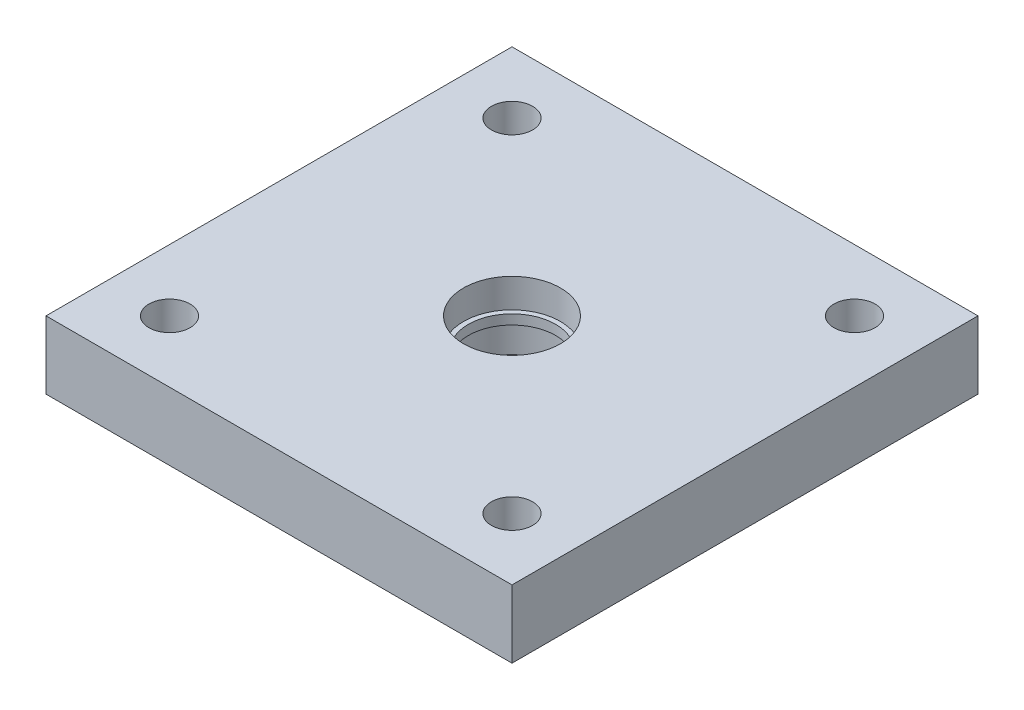
SolidWorks part; units mm, degrees
material "1060 Alloy"
ref_plane "Front" through (0, 0, 0) normal (0, 0, 1) x (1, 0, 0)
ref_plane "Top" through (0, 0, 0) normal (0, 1, 0) x (1, 0, 0)
ref_plane "Right" through (0, 0, 0) normal (1, 0, 0) x (0, 0, -1)
sketch "Sketch1" plane through (0, 0, 0) normal (0, 1, 0) x (1, 0, 0)
  line L1 (-48.1053, 48.1053) -> (48.1053, 48.1053)
  line L2 (-48.1053, 48.1053) -> (-48.1053, -48.1053)
  line L3 (-48.1053, -48.1053) -> (48.1053, -48.1053)
  line L4 (48.1053, 48.1053) -> (48.1053, -48.1053)
  line L5 (-48.1053, 48.1053) -> (48.1053, -48.1053) construction
  line L6 (-48.1053, -48.1053) -> (48.1053, 48.1053) construction
  circle A0 centre (-35.3553, 35.3553) radius 4.25
  circle A1 centre (35.3553, 35.3553) radius 4.25
  circle A2 centre (35.3553, -35.3553) radius 4.25
  circle A3 centre (-35.3553, -35.3553) radius 4.25
  circle A4 centre (0, 0) radius 9
  point P0 (0, 0)
  point P17 (0, 0)
  dimension "D3" = 8.5
  dimension "D7" = 18
  dimension "D2" = 50
  dimension "D5" = 50
  dimension "D6" = 50
  dimension "D1" = 12.75
  dimension "D4" = 4
extrude "body and main holes" add sketch "Sketch1" along normal blind 14
sketch "Sketch2" plane through (0, 14, 0) normal (0, 1, 0) x (1, 0, 0)
  circle A0 centre (0, 0) radius 10
  dimension "D1" = 20
extrude "seal hole" cut sketch "Sketch2" against normal blind 6
sketch "Sketch3" plane through (0, 0, 0) normal (0, -1, 0) x (1, 0, 0)
  circle A0 centre (0, 0) radius 10
  dimension "D1" = 20
extrude "bearing hole" cut sketch "Sketch3" against normal blind 6
sketch "Sketch4" plane through (0, 0, 0) normal (0, -1, 0) x (1, 0, 0)
  circle A0 centre (0, 0) radius 15 construction
  circle A1 centre (0, -15) radius 2
  circle A2 centre (-15, 0) radius 2
  circle A3 centre (0, 15) radius 2
  circle A4 centre (15, 0) radius 2
  point P14 (0, 0)
  dimension "D1" = 30
  dimension "D2" = 4
  dimension "D3" = 4
extrude "Cut-Extrude1" cut sketch "Sketch4" against normal blind 10
equation "\"motor mount pattern diameter\"= 30mm"
equation "\"D2@Sketch1\" = \"motor mount to housing m8 pattern diameter\" / 2"
equation "\"D3@Sketch1\" = \"motor mount to housing m8 screw hole diameter\""
equation "\"D5@Sketch1\" = \"motor mount to housing m8 pattern diameter\" / 2"
equation "\"D6@Sketch1\" = \"motor mount to housing m8 pattern diameter\" / 2"
equation "\"D1@Sketch1\" = \"motor mount to housing m8 screw post radius\""
equation "\"D1@body and main holes\" = \"housing base thickness\""
equation "\"D1@Sketch2\" = \"seal OD\""
equation "\"D1@seal hole\" = \"seal depth\""
equation "\"D1@Sketch3\" = \"bearing OD\""
equation "\"D1@bearing hole\" = \"bearing depth\""
equation "\"bearing OD\" = 20mm"
equation "\"bearing outer race thickness\"= 1mm"
equation "\"bearing ID\"= 10mm"
equation "\"bearing depth\"= 6mm"
equation "\"bearing inner race thickness\"= 1mm"
equation "\"seal OD\" = 20mm"
equation "\"seal ID\"= 8mm"
equation "\"seal depth\"= 6mm"
equation "\"impeller base outer diameter\"= 1.75in"
equation "\"impeller base outer thickness\"= 1mm"
equation "\"impeller base center thickness\"= 5mm"
equation "\"impeller number of vanes\"= 8"
equation "\"impeller vane inner height\"= 8mm"
equation "\"impeller primary vane opening diamater\"= 10mm"
equation "\"impeller vane inner thickness\"= .75mm"
equation "\"impeller vane outer thickness\"= 1.5mm"
equation "\"impeller primary vane entrance angle\"= 20deg"
equation "\"impeller secondary vane entrance angle\"= 20deg"
equation "\"impeller secondary vane opening diameter\"= 10mm"
equation "\"motor to housing distance\"= 60mm"
equation "\"motor mount coupler shaft hole diameter\"= \"coupler shaft base diameter\"+ 4mm"
equation "\"motor mount to housing m8 screw hole diameter\"= 8.5mm"
equation "\"motor mount to housing m8 screw post radius\"= ( 3 * \"motor mount to housing m8 screw hole diameter\" ) / 2"
equation "\"motor mount to housing m8 pattern diameter\"= 100mm"
equation "\"motor mount to housing m4 screw hole diamater\"= 4mm"
equation "\"motor mount to housing m4 head diameter\"= 7.25mm"
equation "\"motor mount to housing m4 head depth\"= 4mm"
equation "\"motor mount plate thickness\"= 6mm + \"motor mount to housing m4 head depth\""
equation "\"coupler shaft set screw 1 distance\"= \"motor mount shaft hole depth\" / 3"
equation "\"coupler shaft set screw 2 distance\"= \"motor mount shaft hole depth\" * 4 / 5"
equation "\"housing bearing seat lip thickness\" = 2mm"
equation "\"housing base thickness\"= \"housing bearing seat lip thickness\" + \"seal depth\" + \"bearing depth\""
equation "\"housing top impeller vertical clearance\"= .5mm"
equation "\"housing top impeller horizontal clearance\"= .5mm"
equation "\"housing top impeller bottom clearance\"= 1mm"
equation "\"housing top impeller cavity height\"= \"housing top impeller bottom clearance\" + \"impeller base center thickness\" + \"impeller vane inner height\" + \"housing top impeller vertical clearance\""
equation "\"housing top impeller cavity diameter\"= 2 * \"housing top impeller horizontal clearance\" + \"impeller base outer diameter\""
equation "\"housing top impeller cavity tip height\"= \"housing top impeller bottom clearance\" + \"housing top impeller vertical clearance\" + \"impeller base outer thickness\" + \"impeller vane outer height\""
equation "\"housing top entrance OD\"= 20mm"
equation "\"housing top exit OD\"= 5mm"
equation "\"housing top o-ring channel height\"= 1.5mm"
equation "\"housing top o ring channel width\"= 1.5mm"
equation "\"housing top threaded inlet depth\"= 8mm"
equation "\"housing top total thickness\"= \"housing top threaded inlet depth\" + \"housing top impeller cavity height\""
equation "\"housing top total width\"= 10mm"
equation "\"housing top exit threaded diameter\"= 8mm"
equation "\"housing top exit threaded depth\"= 8mm"
equation "\"motor shaft pride\"= 32mm"
equation "\"motor shaft flat section length from tip\"= 25.7mm"
equation "\"motor shaft bore end clearance\"= 2mm"
equation "\"motor mount shaft hole depth\"= \"motor shaft pride\""
equation "\"coupler shaft set screw drill hole diameter\"= 6mm"
equation "\"coupler shaft motor shaft hole diameter\"= 8mm"
equation "\"coupler shaft base diameter\"= 18mm"
equation "\"coupler shaft base length\"= \"motor mount shaft hole depth\" + 10mm"
equation "\"coupler shaft second section diameter\"= \"bearing ID\" + \"bearing inner race thickness\" * 2"
equation "\"coupler shaft second section length\"= \"motor to housing distance\" -  \"coupler shaft base length\" - 2mm"
equation "\"coupler shaft third section diamater\"= \"bearing ID\""
equation "\"coupler shaft third section length\"= \"bearing depth\""
equation "\"coupler shaft seal section diameter\" = \"seal ID\""
equation "\"coupler shaft seal section length\" = \"housing base thickness\"+\"housing top impeller bottom clearance\"-\"bearing depth\""
equation "\"coupler shaft impeller section diameter\" = 6mm"
equation "\"coupler shaft impeller section length\" = \"impeller boss depth\"+\"impeller base center thickness\" - 1mm"
equation "\"coupler shaft impeller screw hole diameter\" = \"motor mount to housing m4 screw hole diamater\""
equation "\"coupler shaft impeller screw hole depth\" = 10mm"
equation "\"D7@Sketch1\"=\"bearing OD\"-\"bearing outer race thickness\"*2"
equation "\"D1@Sketch4\"=\"bearing OD\"+ 10mm"
equation "\"D2@Sketch4\"=\"motor mount to housing m4 screw hole diamater\""
equation "\"D1@Cut-Extrude1\"=\"housing base thickness\"-4mm"
equation "\"impeller vane outer height\"= 4mm"
equation "\"impeller bolt surface height\" = 5mm"
equation "\"impeller bolt surface diameter\" = 8mm"
equation "\"impeller boss depth\" = 5mm"
equation "\"impeller dowel diameter\" = 2mm"
equation "\"housing top o-ring circumference\" = 250mm"
equation "\"housing top o-ring radius\" = (\"housing top o-ring circumference\")/(2*3.14)"
equation "\"coupler shaft to motor clearance\" = 2mm"
equation "\"impeller boss diameter\" = \"coupler shaft impeller section diameter\"+2*5mm"
equation "\"impeller dowel length\" = 2mm*2 + \"coupler shaft impeller section diameter\""
